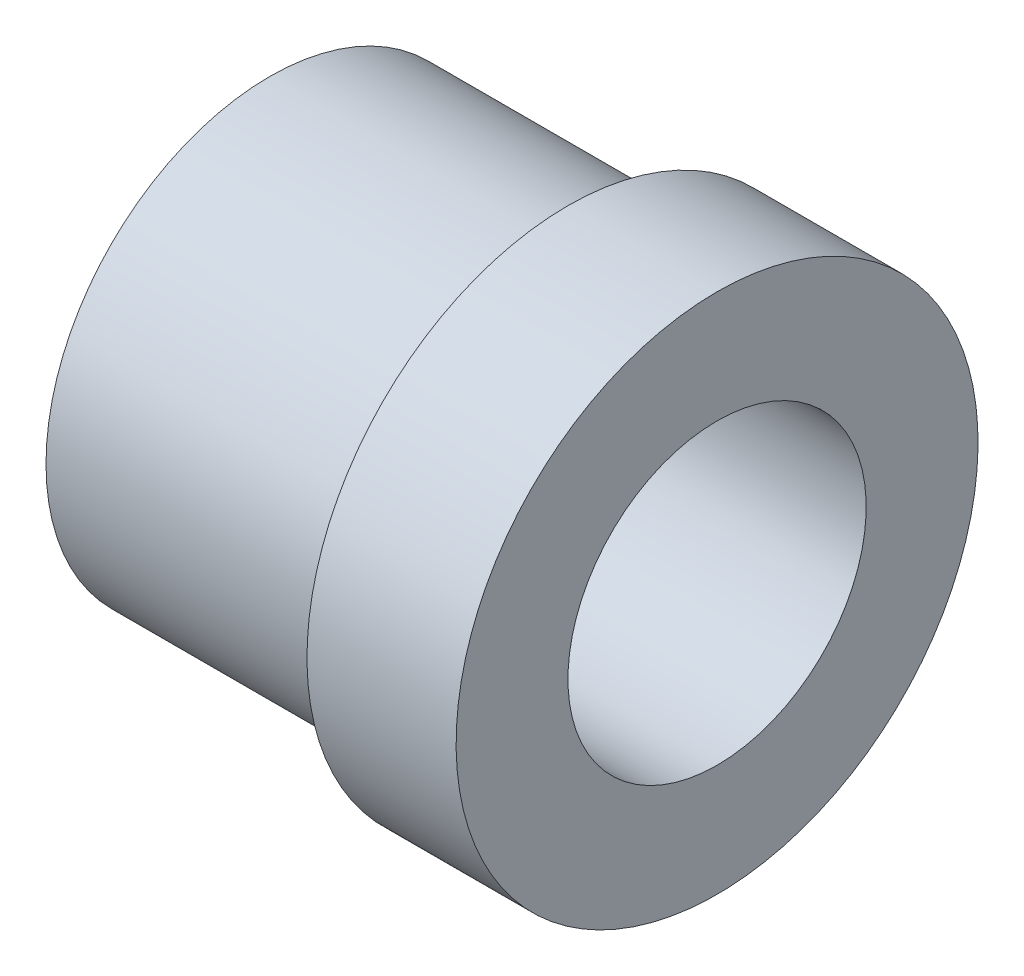
SolidWorks part; units mm, degrees
ref_plane "Front Plane" through (0, 0, 0) normal (0, 0, 1) x (1, 0, 0)
ref_plane "Top Plane" through (0, 0, 0) normal (0, 1, 0) x (1, 0, 0)
ref_plane "Right Plane" through (0, 0, 0) normal (1, 0, 0) x (0, 0, -1)
sketch "Sketch2" plane through (0, 0, 0) normal (0, 0, 1) x (1, 0, 0)
  line L0 (-6, 0) -> (-6, 3)
  line L1 (-6, 3) -> (-2, 3)
  line L2 (-2, 3) -> (-2, 3.5)
  line L3 (-2, 3.5) -> (0, 3.5)
  line L4 (0, 3.5) -> (0, 0)
  line L5 (0, 0) -> (-6, 0)
  dimension "D1" = 3.5
  dimension "D2" = 2
  dimension "D3" = 4
  dimension "D4" = 3
revolve "Revolve1" add sketch "Sketch2" angle 360 about L5
sketch "Sketch3" plane through (0, 0, 0) normal (1, 0, 0) x (0, 0, -1)
  circle A0 centre (0, 0) radius 2
  dimension "D1" = 4
extrude "Cut-Extrude1" cut sketch "Sketch3" against normal through all
